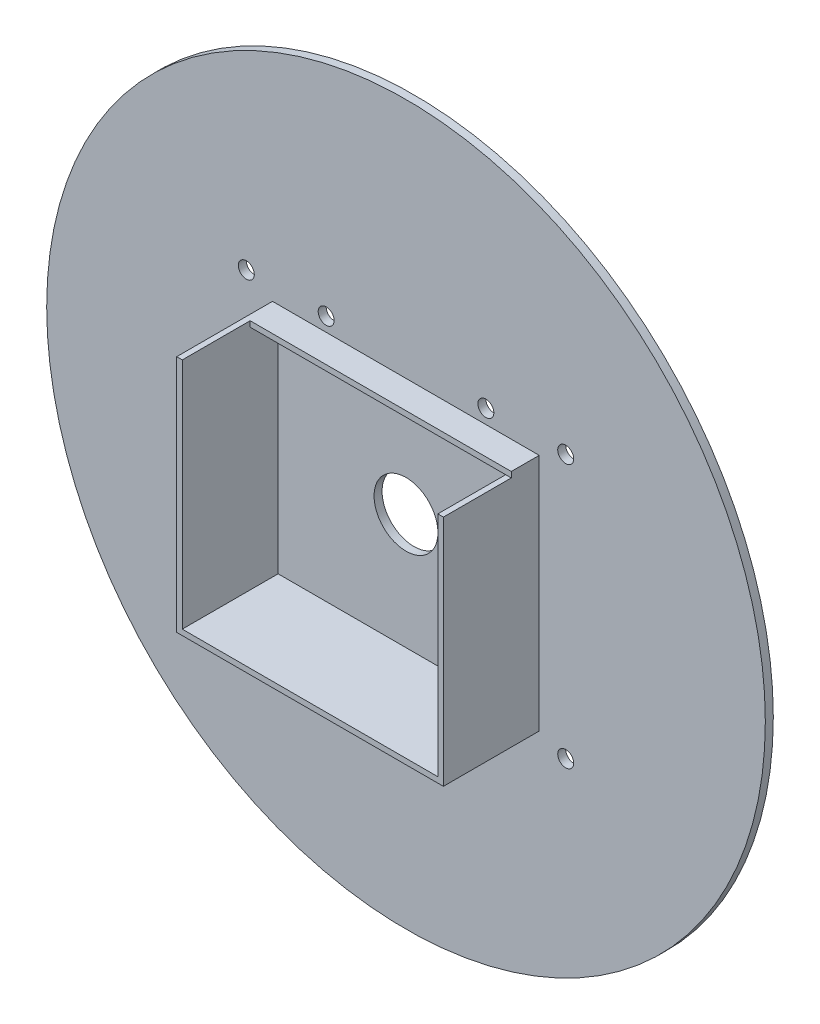
SolidWorks part; units mm, degrees
material "铸造合金钢"
ref_plane "前视基准面" through (0, 0, 0) normal (0, 0, 1) x (1, 0, 0)
ref_plane "上视基准面" through (0, 0, 0) normal (0, 1, 0) x (1, 0, 0)
ref_plane "右视基准面" through (0, 0, 0) normal (1, 0, 0) x (0, 0, -1)
sketch "草图1" plane through (0, 0, 0) normal (0, 0, 1) x (1, 0, 0)
  circle A0 centre (0, 0) radius 45
  dimension "D1" = 90
extrude "凸台-拉伸1" add sketch "草图1" along normal blind 1
sketch "草图2" plane through (0, 0, 1) normal (0, 0, 1) x (1, 0, 0)
  line L1 (-20, 16.5) -> (20, 16.5) construction
  line L2 (-20, 16.5) -> (-20, -16.5) construction
  line L3 (-20, -16.5) -> (20, -16.5) construction
  line L4 (20, 16.5) -> (20, -16.5) construction
  line L5 (-20, 16.5) -> (20, -16.5) construction
  line L6 (-20, -16.5) -> (20, 16.5) construction
  circle A0 centre (20, -16.5) radius 1
  circle A1 centre (20, 16.5) radius 1
  circle A2 centre (-20, 16.5) radius 1
  circle A3 centre (-20, -16.5) radius 1
  circle A4 centre (10, -16.5) radius 1
  circle A5 centre (10, 16.5) radius 1
  circle A6 centre (-10, 16.5) radius 1
  circle A7 centre (-10, -16.5) radius 1
  point P0 (0, 0)
  dimension "D3" = 2
  dimension "D4" = 2
  dimension "D5" = 2
  dimension "D6" = 2
  dimension "D7" = 10
  dimension "D8" = 10
  dimension "D9" = 2
  dimension "D10" = 2
  dimension "D11" = 2
  dimension "D12" = 2
  dimension "D13" = 10
  dimension "D14" = 10
  dimension "D1" = 40
  dimension "D2" = 33
extrude "切除-拉伸1" cut sketch "草图2" against normal through all
sketch "草图4" plane through (0, 0, 1) normal (0, 0, 1) x (1, 0, 0)
  circle A0 centre (0, 0) radius 4
  dimension "D1" = 8
extrude "切除-拉伸2" cut sketch "草图4" against normal through all
sketch "草图5" plane through (0, 0, 1) normal (0, 0, 1) x (1, 0, 0)
  line L0 (15.9814, 14.0362) -> (16.6814, 14.0362)
  line L1 (-16.0186, 14.0362) -> (15.9814, 14.0362)
  line L2 (-16.0186, 14.0362) -> (-16.0186, -14.4638)
  line L3 (-16.0186, -14.4638) -> (15.9814, -14.4638)
  line L4 (15.9814, 14.0362) -> (15.9814, -14.4638)
  line L5 (-16.7186, 14.7362) -> (16.6814, 14.7362)
  line L6 (-16.7186, 14.7362) -> (-16.7186, -15.1638)
  line L7 (-16.7186, -15.1638) -> (16.6814, -15.1638)
  line L8 (16.6814, 14.7362) -> (16.6814, 14.0362)
  line L9 (15.9814, -14.4638) -> (16.6814, -14.4638)
  line L10 (16.6814, -14.4638) -> (16.6814, -15.1638)
  line L11 (16.6814, -14.4638) -> (16.6814, 14.0362)
  dimension "D1" = 32
  dimension "D2" = 28.5
  dimension "D3" = 0.7
  dimension "D4" = 0.7
  dimension "D5" = 0.7
  dimension "D6" = 0.7
extrude "拉伸-薄壁2" add sketch "草图5" along normal blind 12 thin contours L11
sketch "草图9" plane through (0, 0, 1) normal (0, 0, 1) x (1, 0, 0)
  line L0 (16.6814, 14.0362) -> (16.6814, 14.7362)
  line L1 (15.9814, 14.0362) -> (-16.0186, 14.0362)
  line L2 (-16.0186, 14.0362) -> (-16.0186, -14.4638)
  line L3 (-16.0186, -14.4638) -> (15.9814, -14.4638)
  line L4 (16.6814, -13.7638) -> (16.6814, -14.4638)
  line L5 (16.6814, 14.7362) -> (-16.0186, 14.7362)
  line L6 (-16.0186, 14.7362) -> (-16.0186, 14.0362)
  line L7 (16.6814, -14.4638) -> (16.6814, -15.1638)
  line L8 (16.6814, -15.1638) -> (-16.0186, -15.1638)
  line L9 (-16.0186, -15.1638) -> (-16.0186, -14.4638)
  line L10 (-16.0186, -15.1638) -> (-16.7186, -15.1638)
  line L11 (-16.7186, -15.1638) -> (-16.7186, 14.7362)
  line L12 (-16.7186, 14.7362) -> (-16.0186, 14.7362)
  line M18 (15.9814, 14.0362) -> (16.6814, 14.0362)
  dimension "D1" = 0.7
  dimension "D2" = 0.7
  dimension "D3" = 0.7
  dimension "D4" = 32
extrude "凸台-拉伸2" add sketch "草图9" along normal blind 3.5 contours L5 L6 L1 L0 M18
sketch "草图10" plane through (0, 0, 1) normal (0, 0, 1) x (1, 0, 0)
  line L0 (16.6814, -14.4638) -> (16.6814, -15.1638)
  line L1 (16.6814, -15.1638) -> (-16.7186, -15.1638)
  line L2 (-16.7186, -15.1638) -> (-16.7186, 14.7362)
  line L3 (-16.7186, 14.7362) -> (-16.0186, 14.7362)
  line L4 (-16.0186, 14.7362) -> (-16.0186, -14.4638)
  line L5 (-16.0186, -14.4638) -> (15.9814, -14.4638)
  line L6 (15.9814, -14.4638) -> (16.6814, -14.4638)
  dimension "D1" = 0.7
  dimension "D2" = 0.7
extrude "凸台-拉伸3" add sketch "草图10" along normal blind 12
